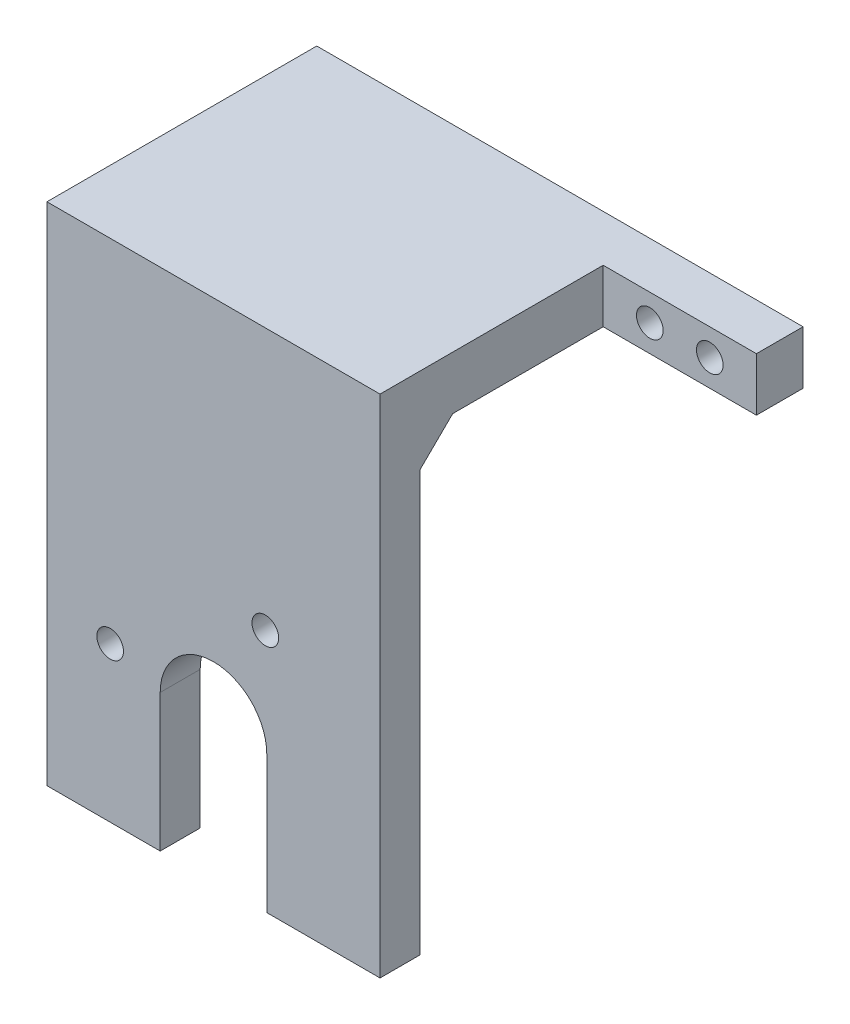
SolidWorks part; units mm, degrees
material "ABS"
ref_plane "Front Plane" through (0, 0, 0) normal (0, 0, 1) x (1, 0, 0)
ref_plane "Top Plane" through (0, 0, 0) normal (0, 1, 0) x (1, 0, 0)
ref_plane "Right Plane" through (0, 0, 0) normal (1, 0, 0) x (0, 0, -1)
sketch "Sketch1" plane through (0, 0, 0) normal (0, 0, 1) x (1, 0, 0)
  line L1 (-37.3941, 10.9555) -> (12.6059, 10.9555)
  line L2 (-37.3941, 10.9555) -> (-37.3941, -7.0445)
  line L3 (-37.3941, -7.0445) -> (12.6059, -7.0445)
  line L4 (12.6059, 10.9555) -> (12.6059, -7.0445)
  dimension "D1" = 50
  dimension "D2" = 18
extrude "Boss-Extrude1" add sketch "Sketch1" along normal blind 7
sketch "Sketch2" plane through (0, 0, 7) normal (0, 0, 1) x (1, 0, 0)
  line L0 (12.6059, -7.0445) -> (12.6059, 10.9555) construction
  line L1 (-37.3941, 10.9555) -> (12.6059, 10.9555)
  line L2 (-37.3941, 10.9555) -> (-37.3941, 2.9555)
  line L3 (-37.3941, 2.9555) -> (12.6059, 2.9555)
  line L4 (12.6059, 10.9555) -> (12.6059, 2.9555)
  dimension "D1" = 8
extrude "Boss-Extrude2" add sketch "Sketch2" along normal blind 33.5
sketch "Sketch3" plane through (12.6059, 0, 0) normal (1, 0, 0) x (0, 0, -1)
  line L0 (-40.5, 10.9555) -> (0, 10.9555) construction
  line L1 (-7, 2.9555) -> (0, 2.9555)
  line L2 (-7, 2.9555) -> (-7, 10.9555)
  line L3 (-7, 10.9555) -> (0, 10.9555)
  line L4 (0, 2.9555) -> (0, 10.9555)
extrude "Boss-Extrude3" add sketch "Sketch3" along normal blind 23
sketch "Sketch4" plane through (-37.3941, 0, 0) normal (-1, 0, 0) x (0, 0, 1)
  line L1 (7, 2.9555) -> (0, 2.9555)
  line L2 (7, 2.9555) -> (7, 10.9555)
  line L3 (7, 10.9555) -> (0, 10.9555)
  line L4 (0, 2.9555) -> (0, 10.9555)
extrude "Boss-Extrude4" add sketch "Sketch4" along normal blind 14
sketch "Sketch5" plane through (0, 0, 7) normal (0, 0, 1) x (1, 0, 0)
  line L1 (-37.3941, -7.0445) -> (12.6059, -7.0445)
  line L2 (-37.3941, -7.0445) -> (-37.3941, 2.9555)
  line L3 (-37.3941, 2.9555) -> (12.6059, 2.9555)
  line L4 (12.6059, -7.0445) -> (12.6059, 2.9555)
extrude "Cut-Extrude1" cut sketch "Sketch5" against normal blind 14
sketch "Sketch6" plane through (0, 0, 7) normal (0, 0, 1) x (1, 0, 0)
  line L0 (35.6059, 10.9555) -> (35.6059, 2.9555) construction
  line L2 (-51.3941, 2.9555) -> (-37.3941, 2.9555) construction
  line L3 (35.6059, 2.9555) -> (12.6059, 2.9555) construction
  circle A0 centre (19.6059, 6.9555) radius 2
  circle A1 centre (28.6059, 6.9555) radius 2
  dimension "D1" = 4
  dimension "D2" = 4
  dimension "D3" = 7
  dimension "D4" = 9
  dimension "D5" = 4
  dimension "D6" = 4
extrude "Cut-Extrude2" cut sketch "Sketch6" against normal blind 14
sketch "Sketch7" plane through (0, 2.9555, 0) normal (0, -1, 0) x (1, 0, 0)
  line L0 (12.6059, 40.5) -> (12.6059, 7) construction
  line L1 (-37.3941, 40.5) -> (12.6059, 40.5)
  line L2 (-37.3941, 40.5) -> (-37.3941, 34.5)
  line L3 (-37.3941, 34.5) -> (12.6059, 34.5)
  line L4 (12.6059, 40.5) -> (12.6059, 34.5)
  dimension "D1" = 6
extrude "Boss-Extrude5" add sketch "Sketch7" along normal blind 67.91
sketch "Sketch8" plane through (0, 0, 40.5) normal (0, 0, 1) x (1, 0, 0)
  line L0 (-12.3941, -44.3312) -> (-12.3941, -64.9545) construction
  line L1 (12.6059, -64.9545) -> (-37.3941, -64.9545) construction
  line L2 (-4.3941, -44.3312) -> (-4.3941, -64.9545)
  line L3 (-20.3941, -44.3312) -> (-20.3941, -64.9545)
  line L4 (-37.3941, 10.9555) -> (-37.3941, -64.9545) construction
  arc A0 (-4.3941, -44.3312) -> (-20.3941, -44.3312) centre (-12.3941, -44.3312) ccw
  arc A1 (-20.3941, -64.9545) -> (-4.3941, -64.9545) centre (-12.3941, -64.9545) ccw
  point P4 (-12.3941, -54.6428)
  dimension "D3" = 20.6233
  dimension "D1" = 16
  dimension "D2" = 25
extrude "Cut-Extrude3" cut sketch "Sketch8" against normal blind 35
sketch "Sketch9" plane through (0, 0, 34.5) normal (0, 0, -1) x (-1, 0, 0)
  line L0 (-12.6059, -64.9545) -> (4.3941, -64.9545) construction
  line L1 (20.3941, -64.9545) -> (37.3941, -64.9545) construction
  circle A0 centre (27.901, -41.7569) radius 2
  circle A1 centre (4.6167, -28.3707) radius 2
  dimension "D1" = 4
  dimension "D2" = 4
  dimension "D3" = 36.5838
  dimension "D4" = 23.1976
extrude "Cut-Extrude5" cut sketch "Sketch9" against normal blind 35
sketch "Sketch12" plane through (-37.3941, 0, 0) normal (-1, 0, 0) x (0, 0, 1)
  line L0 (34.5, -1.8735) -> (29.5873, 2.9555)
  line L1 (34.5, -64.9545) -> (34.5, 2.9555) construction
  line L2 (34.5, 2.9555) -> (7, 2.9555) construction
  line L3 (29.5873, 2.9555) -> (34.5, 2.9555)
  line L4 (34.5, 2.9555) -> (34.5, -1.8735)
extrude "Boss-Extrude8" add sketch "Sketch12" against normal blind 50
sketch "Sketch13" plane through (0, 0, 7) normal (0, 0, 1) x (1, 0, 0)
  line L1 (-51.3941, 10.9555) -> (-37.3941, 10.9555)
  line L2 (-51.3941, 10.9555) -> (-51.3941, 2.9555)
  line L3 (-51.3941, 2.9555) -> (-37.3941, 2.9555)
  line L4 (-37.3941, 10.9555) -> (-37.3941, 2.9555)
extrude "Cut-Extrude6" cut sketch "Sketch13" against normal blind 10
